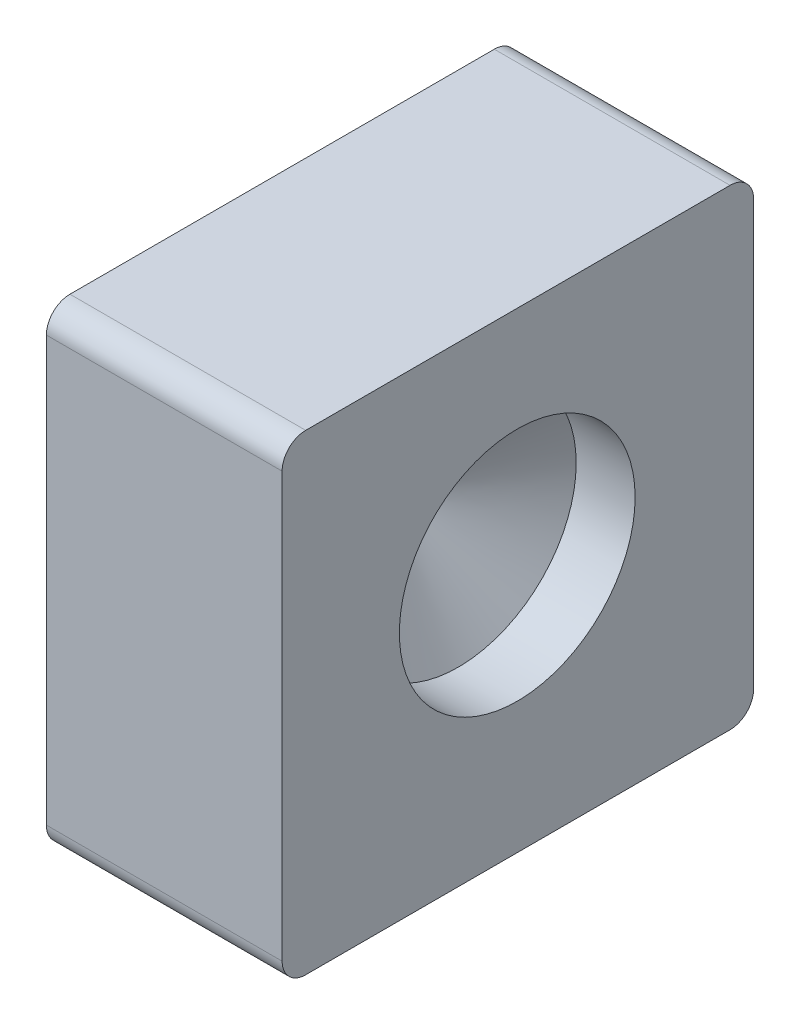
SolidWorks part; units mm, degrees
ref_plane "Front Plane" through (0, 0, 0) normal (0, 0, 1) x (1, 0, 0)
ref_plane "Top Plane" through (0, 0, 0) normal (0, 1, 0) x (1, 0, 0)
ref_plane "Right Plane" through (0, 0, 0) normal (1, 0, 0) x (0, 0, -1)
sketch "Sketch2" plane through (0, 0, 0) normal (1, 0, 0) x (0, 0, -1)
  line L0 (-25.201, 26.8343) -> (20.519, 26.8343)
  line L1 (23.059, 24.2943) -> (23.059, -21.4257)
  line L2 (20.519, -23.9657) -> (-25.201, -23.9657)
  line L3 (-27.741, -21.4257) -> (-27.741, 24.2943)
  arc A0 (-25.201, 26.8343) -> (-27.741, 24.2943) centre (-25.201, 24.2943) ccw
  arc A1 (-25.201, -23.9657) -> (-27.741, -21.4257) centre (-25.201, -21.4257) cw
  arc A2 (23.059, -21.4257) -> (20.519, -23.9657) centre (20.519, -21.4257) cw
  arc A3 (20.519, 26.8343) -> (23.059, 24.2943) centre (20.519, 24.2943) cw
  point P6 (-27.741, 26.8343)
  point P11 (23.059, -23.9657)
  point P14 (23.059, 26.8343)
  dimension "D3" = 2.54
  dimension "D1" = 50.8
  dimension "D2" = 50.8
extrude "Boss-Extrude1" add sketch "Sketch2" along normal blind 25.4
hole_wizard "1 (1.0000) Dowel Hole1" positions "Sketch3" profile "Sketch4" hole size "1" standard "ANSI Inch"
sketch "Sketch3" plane through (25.4, 0, 0) normal (1, 0, 0) x (0, 0, -1)
  point P0 (-2.409, 2.8623)
sketch "Sketch4" plane through (25.4, 2.8623, 2.409) normal (0, 1, 0) x (0, 0, -1)
  line L0 (0, 0) -> (0, 13.9809)
  line L1 (0, 13.9809) -> (12.7, 6.35)
  line L2 (12.7, 6.35) -> (12.7, 0)
  line L5 (12.7, 0) -> (0, 0)
  line L10 (0, 13.9809) -> (-12.7, 6.35) construction
  line L11 (0, -6.35) -> (0, 107.95) construction
  dimension "Hole Dia." = 25.4
  dimension "Hole Depth" = 6.35
  dimension "Drill Angle" = 118
